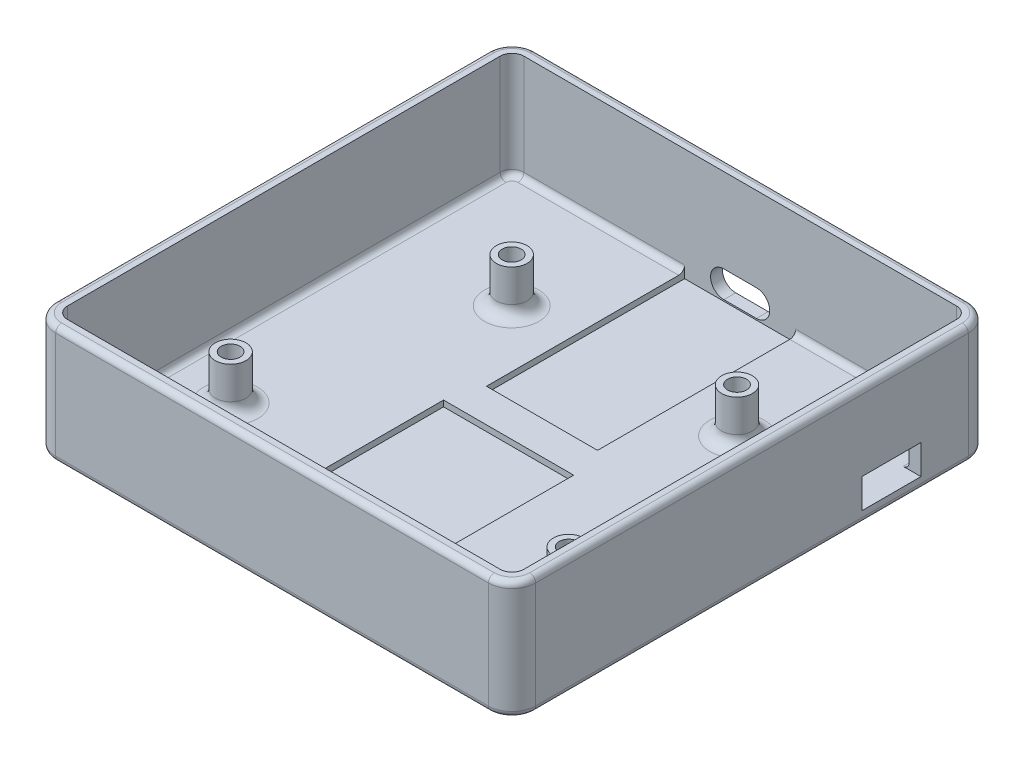
SolidWorks part; units mm, degrees
ref_plane "Front Plane" through (0, 0, 0) normal (0, 0, 1) x (1, 0, 0)
ref_plane "Top Plane" through (0, 0, 0) normal (0, 1, 0) x (1, 0, 0)
ref_plane "Right Plane" through (0, 0, 0) normal (1, 0, 0) x (0, 0, -1)
sketch "Sketch1" plane through (0, 0, 0) normal (0, 1, 0) x (1, 0, 0)
  line L1 (-38.575, -38.575) -> (38.575, -38.575)
  line L2 (-38.575, -38.575) -> (-38.575, 38.575)
  line L3 (-38.575, 38.575) -> (38.575, 38.575)
  line L4 (38.575, -38.575) -> (38.575, 38.575)
  line L5 (-38.575, -38.575) -> (38.575, 38.575) construction
  line L6 (-38.575, 38.575) -> (38.575, -38.575) construction
  point P0 (0, 0)
  dimension "D1" = 77.15
extrude "Boss-Extrude1" add sketch "Sketch1" along normal blind 2
sketch "Sketch2" plane through (0, 0, 0) normal (0, 1, 0) x (1, 0, 0)
  line L20 (38.575, -38.575) -> (38.575, 38.575) construction
  line L21 (38.575, 38.575) -> (-38.575, 38.575) construction
  line L22 (-38.575, 38.575) -> (-38.575, -38.575) construction
  line L23 (-38.575, -38.575) -> (38.575, -38.575) construction
  line L24 (40.575, -40.575) -> (40.575, 40.575)
  line L25 (40.575, 40.575) -> (-40.575, 40.575)
  line L26 (-40.575, 40.575) -> (-40.575, -40.575)
  line L27 (-40.575, -40.575) -> (40.575, -40.575)
  line L28 (40.575, -40.575) -> (40.575, 40.575)
  line L29 (40.575, 40.575) -> (-40.575, 40.575)
  line L30 (-40.575, 40.575) -> (-40.575, -40.575)
  line L31 (-40.575, -40.575) -> (40.575, -40.575)
  line L32 (38.575, -38.575) -> (38.575, 38.575)
  line L33 (38.575, 38.575) -> (-38.575, 38.575)
  line L34 (-38.575, 38.575) -> (-38.575, -38.575)
  line L35 (-38.575, -38.575) -> (38.575, -38.575)
  dimension "D1" = 2
extrude "Boss-Extrude2" add sketch "Sketch2" along normal blind 20
sketch "Sketch3" plane through (0, 2, 0) normal (0, 1, 0) x (1, 0, 0)
  line L0 (28.58, -19) -> (-28.58, -19) construction
  line L2 (19.05, 19) -> (-19.05, 19) construction
  circle A2 centre (-28.58, -19) radius 1.6
  circle A3 centre (28.58, -19) radius 1.6
  circle A4 centre (19.05, 19) radius 1.6
  circle A5 centre (-19.05, 19) radius 1.6
  circle A6 centre (-28.58, -19) radius 2.6
  circle A7 centre (-19.05, 19) radius 2.6
  circle A8 centre (28.58, -19) radius 2.6
  circle A9 centre (19.05, 19) radius 2.6
  point P0 (0, 0)
  point P2 (0, 19)
  point P17 (0, -19)
  dimension "D3" = 1
  dimension "D4" = 19
  dimension "D1" = 3.2
  dimension "D2" = 38.1
  dimension "D5" = 57.16
  dimension "D6" = 19
extrude "Boss-Extrude4" add sketch "Sketch3" along normal offset from surface (7.5 mm away) 10.5 up to face at (0, 20, 0)
sketch "Sketch4" plane through (0, 0, 0) normal (1, 0, 0) x (0, 0, -1)
  line L0 (0, 0) -> (0, 20) construction
  line L1 (-40.575, 20) -> (40.575, 20) construction
sketch "Sketch11" plane through (0, 2, 0) normal (0, 1, 0) x (1, 0, 0)
  line L0 (-10, -31.575) -> (-10, -1.575)
  line L6 (-11, -32.575) -> (11, -32.575)
  line L7 (-11, -32.575) -> (-11, -0.575)
  line L8 (-11, -0.575) -> (11, -0.575)
  line L9 (11, -32.575) -> (11, -0.575)
  line L10 (-11, -32.575) -> (11, -0.575) construction
  line L11 (-11, -0.575) -> (11, -32.575) construction
  line L12 (38.575, 38.575) -> (-38.575, 38.575) construction
  line L13 (-8.89, 38.575) -> (8.89, 38.575) construction
  line L14 (-8.89, 38.575) -> (-8.89, 5.575) construction
  line L15 (-8.89, 5.575) -> (8.89, 5.575) construction
  line L16 (8.89, 38.575) -> (8.89, 5.575) construction
  line L17 (-8.89, 38.575) -> (8.89, 5.575) construction
  line L18 (-8.89, 5.575) -> (8.89, 38.575) construction
  line L27 (-10, -1.575) -> (10, -1.575)
  line L28 (10, -31.575) -> (10, -1.575)
  line L29 (-10, -31.575) -> (10, -31.575)
  line L30 (0, -10.45) -> (0, 10.45) construction
  line L31 (4, 38.575) -> (5.5, 38.575)
  line L32 (4, 38.575) -> (4, 10.575)
  line L33 (4, 10.575) -> (5.5, 10.575)
  line L34 (5.5, 38.575) -> (5.5, 10.575)
  line L35 (-4, 10.575) -> (-5.5, 10.575)
  line L36 (-5.5, 38.575) -> (-5.5, 10.575)
  line L37 (-4, 38.575) -> (-5.5, 38.575)
  line L38 (-4, 38.575) -> (-4, 10.575)
  line L39 (-38.575, -38.575) -> (38.575, -38.575) construction
  point P1 (0, 22.075)
  point P6 (0, -16.575)
  dimension "D1" = 33
  dimension "D2" = 17.78
  dimension "D3" = 1
  dimension "D4" = 20
  dimension "D5" = 6
  dimension "D6" = 30
  dimension "D7" = 4
  dimension "D8" = 1.5
  dimension "D9" = 5
extrude "Boss-Extrude7" [suppressed] add sketch "Sketch11" along normal blind 1 contours L35 L36 L37 L38 | L32 L31 L34 L33
sketch "Sketch17" plane through (0, 2, 0) normal (0, 1, 0) x (1, 0, 0)
  line L16 (9.39, 11.075) -> (11.39, 11.075)
  line L17 (11.39, 11.075) -> (11.39, 3.075)
  line L18 (11.39, 3.075) -> (-11.39, 3.075)
  line L19 (-9.39, 5.075) -> (-9.39, 38.575)
  line L20 (9.39, 5.075) -> (-9.39, 5.075)
  line L21 (9.39, 38.575) -> (9.39, 5.075)
  line L22 (-9.39, 5.075) -> (-9.39, 11.075)
  line L23 (9.39, 5.075) -> (-9.39, 5.075)
  line L24 (9.39, 11.075) -> (9.39, 5.075)
  line L25 (-11.39, 3.075) -> (-11.39, 11.075)
  line L26 (-11.39, 11.075) -> (-9.39, 11.075)
  point P0 (0, 0)
  dimension "D1" = 0.5
  dimension "D2" = 2
  dimension "D3" = 2
  dimension "D4" = 8
extrude "Boss-Extrude8" [suppressed] add sketch "Sketch17" along normal blind 2
sketch "Sketch15" plane through (0, 2, 0) normal (0, 1, 0) x (1, 0, 0)
  line L0 (-11, -0.575) -> (-11, -8.575)
  line L1 (-11, -32.575) -> (-11, -0.575) construction
  line L2 (-11, -8.575) -> (-13, -8.575)
  line L3 (-13, -8.575) -> (-13, 1.425)
  line L4 (-13, 1.425) -> (-6, 1.425)
  line L5 (-6, 1.425) -> (-6, -0.575)
  line L6 (-11, -0.575) -> (11, -0.575) construction
  line L7 (-6, -0.575) -> (-11, -0.575)
  line L8 (-13, -24.575) -> (-11, -24.575)
  line L9 (-11, -24.575) -> (-11, -32.575)
  line L10 (-11, -32.575) -> (-6, -32.575)
  line L11 (-11, -32.575) -> (11, -32.575) construction
  line L12 (-6, -32.575) -> (-6, -34.575)
  line L13 (-6, -34.575) -> (-13, -34.575)
  line L14 (-13, -24.575) -> (-13, -34.575)
  line L15 (0, -10.45) -> (0, 10.45) construction
  line L16 (13, -24.575) -> (11, -24.575)
  line L17 (11, -24.575) -> (11, -32.575)
  line L18 (11, -32.575) -> (6, -32.575)
  line L19 (6, -32.575) -> (6, -34.575)
  line L20 (6, -34.575) -> (13, -34.575)
  line L21 (13, -24.575) -> (13, -34.575)
  line L22 (6, 1.425) -> (6, -0.575)
  line L23 (13, 1.425) -> (6, 1.425)
  line L24 (13, -8.575) -> (13, 1.425)
  line L25 (11, -8.575) -> (13, -8.575)
  line L26 (11, -0.575) -> (11, -8.575)
  line L27 (6, -0.575) -> (11, -0.575)
  dimension "D1" = 7
  dimension "D2" = 10
  dimension "D4" = 2
extrude "Boss-Extrude6" [suppressed] add sketch "Sketch15" along normal blind 1.5 contours L7 L0 L2 L3 L4 L5 | L22 L27 L26 L25 L24 L23 | L14 L13 L12 L10 L9 L8 | L16 L17 L18 L19 L20 L21
sketch "Sketch18" plane through (0, 2, 0) normal (0, 1, 0) x (1, 0, 0)
  line L0 (11, -32.575) -> (11, -0.575) construction
  line L1 (-11, -0.575) -> (11, -0.575) construction
  line L2 (-11, -32.575) -> (-11, -0.575) construction
  line L3 (-11, -32.575) -> (11, -32.575) construction
  line L4 (11, -32.575) -> (11, -0.575)
  line L5 (-11, -0.575) -> (11, -0.575)
  line L6 (-11, -32.575) -> (-11, -0.575)
  line L7 (-11, -32.575) -> (11, -32.575)
  line L21 (-8.89, 38.575) -> (8.89, 38.575) construction
  line L22 (-9.39, 38.575) -> (9.39, 38.575)
  line L24 (-9.39, 5.075) -> (-9.39, 38.575)
  line L25 (9.39, 5.075) -> (-9.39, 5.075)
  line L26 (9.39, 38.575) -> (9.39, 5.075)
  line L27 (-9.39, 5.075) -> (-9.39, 38.575)
  line L28 (9.39, 5.075) -> (-9.39, 5.075)
  line L29 (9.39, 38.575) -> (9.39, 5.075)
  point P5 (0, 0)
  point P6 (0, 0)
  point P7 (9.2414, 38.575)
  dimension "D1" = 0.5
extrude "Cut-Extrude4" cut sketch "Sketch18" against normal offset from surface (1 mm away) 1 up to face at (0, 0, 0)
sketch "Sketch7" plane through (0, 0, 0) normal (0, -1, 0) x (1, 0, 0)
  line L0 (40.575, -40.575) -> (-40.575, -40.575) construction
  line L1 (-40.575, -40.575) -> (-40.575, 40.575) construction
  line L2 (0, 0) -> (-24.575, -24.575) construction
  circle A0 centre (-24.575, -24.575) radius 4
  circle A1 centre (-24.575, 24.575) radius 4
  circle A2 centre (24.575, 24.575) radius 4
  circle A3 centre (24.575, -24.575) radius 4
  dimension "D1" = 8
  dimension "D4" = 4
extrude "Cut-Extrude1" cut sketch "Sketch7" against normal offset from surface (1 mm away) 1 up to face at (28.58, 2, 16.4)
sketch "Sketch10" plane through (0, 0, -38.575) normal (0, 0, -1) x (-1, 0, 0)
  line L0 (-2.75, 3.5) -> (2.75, 3.5) construction
  line L1 (-2.75, 5.75) -> (2.75, 5.75)
  line L2 (-2.75, 1.25) -> (2.75, 1.25)
  line L3 (-38.575, 2) -> (-9.39, 2) construction
  line L4 (-38.575, 2) -> (-9.39, 2) construction
  line L5 (-9.39, 1) -> (9.39, 1) construction
  arc A1 (-2.75, 5.75) -> (-2.75, 1.25) centre (-2.75, 3.5) ccw
  arc A2 (2.75, 1.25) -> (2.75, 5.75) centre (2.75, 3.5) ccw
  point P2 (0, 3.5)
  dimension "D1" = 5.5
  dimension "D2" = 4.5
  dimension "D3" = 2.5
extrude "Cut-Extrude2" cut sketch "Sketch10" along normal up to surface (2 mm away) up to face at (0, 10, -40.575)
sketch "Sketch16" plane through (38.575, 0, 0) normal (-1, 0, 0) x (0, 0, 1)
  line L0 (38.575, 2) -> (-38.575, 2) construction
  line L1 (-28.575, 2) -> (-18.575, 2)
  line L2 (-28.575, 2) -> (-28.575, 7)
  line L3 (-28.575, 7) -> (-18.575, 7)
  line L4 (-18.575, 2) -> (-18.575, 7)
  dimension "D1" = 10
  dimension "D2" = 5
  dimension "D3" = 10
extrude "Cut-Extrude3" cut sketch "Sketch16" against normal up to surface (2 mm away) up to face at (40.575, 10, 0)
fillet "Fillet1" radius 2 4 edges at (28.58, 2, 16.4) (19.05, 2, -21.6) (-28.58, 2, 16.4) (-19.05, 2, -21.6)
fillet "Fillet2" [suppressed] radius 1
chamfer "Chamfer1" [suppressed] distance 2.5 angle 45
fillet "Fillet3" [suppressed] radius 2
fillet "Fillet6" radius 4 4 edges at (40.575, 10, -40.575) (-40.575, 10, -40.575) (-40.575, 10, 40.575) (40.575, 10, 40.575)
fillet "Fillet7" radius 2 4 edges at (38.575, 11, -38.575) (-38.575, 11, -38.575) (-38.575, 11, 38.575) (38.575, 11, 38.575)
fillet "Fillet5" radius 1 16 edges at (0, 20, 40.575) (-40.575, 20, 0) (0, 20, -40.575) (0, 0, 40.575) (-40.575, 0, 0) (0, 0, -40.575) (40.575, 20, 0) (40.575, 0, 0) (39.4034, 0, 39.4034) (-39.4034, 0, 39.4034) (-39.4034, 0, -39.4034) (39.4034, 0, -39.4034) (39.4034, 20, 39.4034) (-39.4034, 20, 39.4034) (-39.4034, 20, -39.4034) (39.4034, 20, -39.4034)
fillet "Fillet9" radius 1 10 edges at (22.9825, 2, -38.575) (37.9892, 2, -37.9892) (38.575, 2, 9) (37.9892, 2, 37.9892) (0, 2, 38.575) (-37.9892, 2, 37.9892) (-38.575, 2, 0) (-37.9892, 2, -37.9892) (38.575, 2, -32.575) (-22.9825, 2, -38.575)
